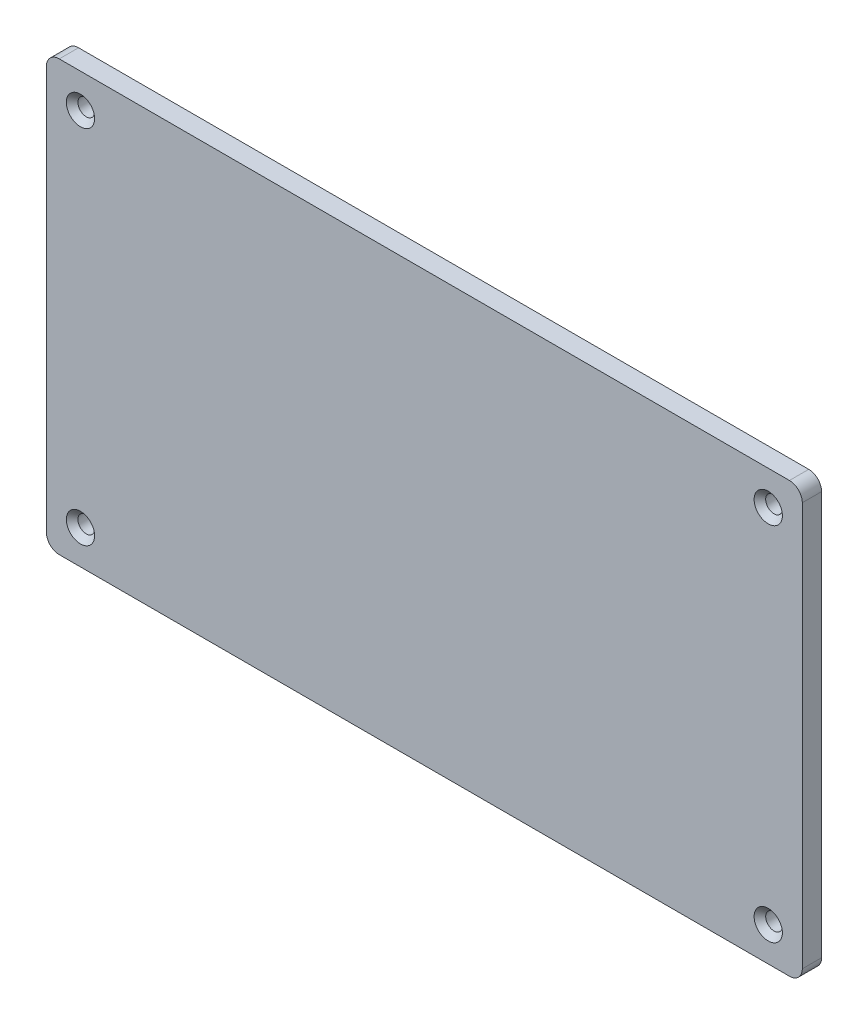
SolidWorks part; units mm, degrees
ref_plane "Piano frontale" through (0, 0, 0) normal (0, 0, 1) x (1, 0, 0)
ref_plane "Piano superiore" through (0, 0, 0) normal (0, 1, 0) x (1, 0, 0)
ref_plane "Piano destro" through (0, 0, 0) normal (1, 0, 0) x (0, 0, -1)
sketch "Schizzo1" plane through (0, 0, 0) normal (0, 0, 1) x (1, 0, 0)
  line L1 (-58.8, -33.4) -> (58.8, -33.4)
  line L2 (-58.8, -33.4) -> (-58.8, 33.4)
  line L3 (-58.8, 33.4) -> (58.8, 33.4)
  line L4 (58.8, -33.4) -> (58.8, 33.4)
  line L5 (-58.8, -33.4) -> (58.8, 33.4) construction
  line L6 (-58.8, 33.4) -> (58.8, -33.4) construction
  point P0 (0, 0)
  dimension "D1" = 117.6
  dimension "D2" = 66.8
extrude "Estrusione-Estrusione1" add sketch "Schizzo1" along normal blind 3
fillet "Raccordo1" radius 2 1 edges at (-58.8, 33.4, 1.5)
fillet "Raccordo2" radius 2 1 edges at (58.8, 33.4, 1.5)
fillet "Raccordo3" radius 2 1 edges at (58.8, -33.4, 1.5)
fillet "Raccordo4" radius 2 1 edges at (-58.8, -33.4, 1.5)
hole_wizard "Foro svasato per Vite M2-1" positions "Schizzo2" profile "Schizzo3" countersink size "M2" standard "Ansi Metric" end condition up to next
sketch "Schizzo2" plane through (0, 0, 3) normal (0, 0, 1) x (1, 0, 0)
  line L0 (-58.8, 31.4) -> (-58.8, -31.4) construction
  line L1 (56.8, 33.4) -> (-56.8, 33.4) construction
  line L2 (58.8, -31.4) -> (58.8, 31.4) construction
  line L3 (-56.8, -33.4) -> (56.8, -33.4) construction
  point P0 (53.5, 28.1)
  point P2 (-53.5, 28.1)
  point P4 (-53.5, -28.1)
  point P6 (53.5, -28.1)
  dimension "D1" = 5.3
  dimension "D2" = 5.3
  dimension "D3" = 5.3
  dimension "D4" = 5.3
  dimension "D5" = 5.3
  dimension "D6" = 5.3
  dimension "D7" = 5.3
  dimension "D8" = 5.3
sketch "Schizzo3" plane through (53.5, 28.1, 3) normal (1, 0, 0) x (0, -1, 0)
  line L0 (0, 0) -> (0, 3)
  line L1 (0, 3) -> (1.3, 3)
  line L2 (1.3, 3) -> (1.3, 0.9)
  line L3 (1.3, 0.9) -> (2.2, 0)
  line L5 (2.2, 0) -> (0, 0)
  line L6 (-1.3, 0.9) -> (-2.2, 0) construction
  line L11 (0, -6.35) -> (0, 107.95) construction
  dimension "Thru Hole Dia." = 2.6
  dimension "Thru Hole Depth" = 3
  dimension "Near C'Sink Dia." = 4.4
  dimension "Near C'Sink Angle" = 90
